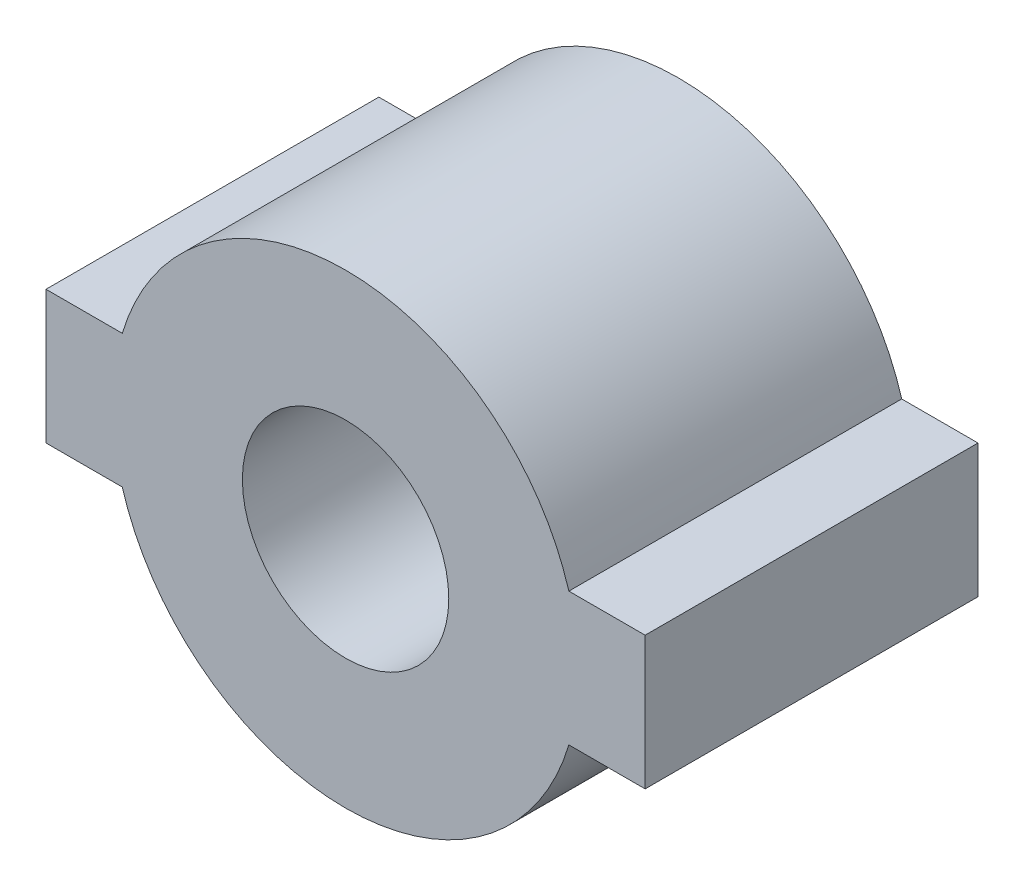
SolidWorks part; units mm, degrees
ref_plane "前基準面" through (0, 0, 0) normal (0, 0, 1) x (1, 0, 0)
ref_plane "上基準面" through (0, 0, 0) normal (0, 1, 0) x (1, 0, 0)
ref_plane "右基準面" through (0, 0, 0) normal (1, 0, 0) x (0, 0, -1)
sketch "草圖1" plane through (0, 0, 0) normal (0, 0, 1) x (1, 0, 0)
  line L0 (0, 0) -> (0, 9.1566) construction
  line L1 (-4.5, 1) -> (-3.3541, 1)
  line L2 (-4.5, 1) -> (-4.5, -1)
  line L3 (-4.5, -1) -> (-3.3541, -1)
  line L4 (4.5, 1) -> (4.5, -1)
  line L5 (0, 0) -> (7.2106, 0) construction
  line L6 (3.3541, 1) -> (4.5, 1)
  line L7 (3.3541, -1) -> (4.5, -1)
  line L8 (-4.3, 0.8) -> (-4.3, -0.8) construction
  line L9 (-4.3, -0.8) -> (-3.2016, -0.8) construction
  line L10 (3.2016, -0.8) -> (4.3, -0.8) construction
  line L11 (4.3, 0.8) -> (4.3, -0.8) construction
  line L12 (3.2016, 0.8) -> (4.3, 0.8) construction
  line L13 (-4.3, 0.8) -> (-3.2016, 0.8) construction
  circle A0 centre (0, 0) radius 6
  arc A1 (3.3541, 1) -> (-3.3541, 1) centre (0, 0) ccw
  arc A2 (-3.3541, -1) -> (3.3541, -1) centre (0, 0) ccw
  arc A3 (-3.2016, -0.8) -> (3.2016, -0.8) centre (0, 0) ccw construction
  arc A4 (3.2016, 0.8) -> (-3.2016, 0.8) centre (0, 0) ccw construction
  circle A5 centre (0, 0) radius 1.55
  dimension "D1" = 12
  dimension "D2" = 7
  dimension "D6" = 3.1
  dimension "D3" = 9
  dimension "D4" = 2
  dimension "D5" = 0.2
extrude "填料-伸長1" add sketch "草圖1" along normal blind 5 contours L3 A2 L7 L4 L6 A1 L1 L2
